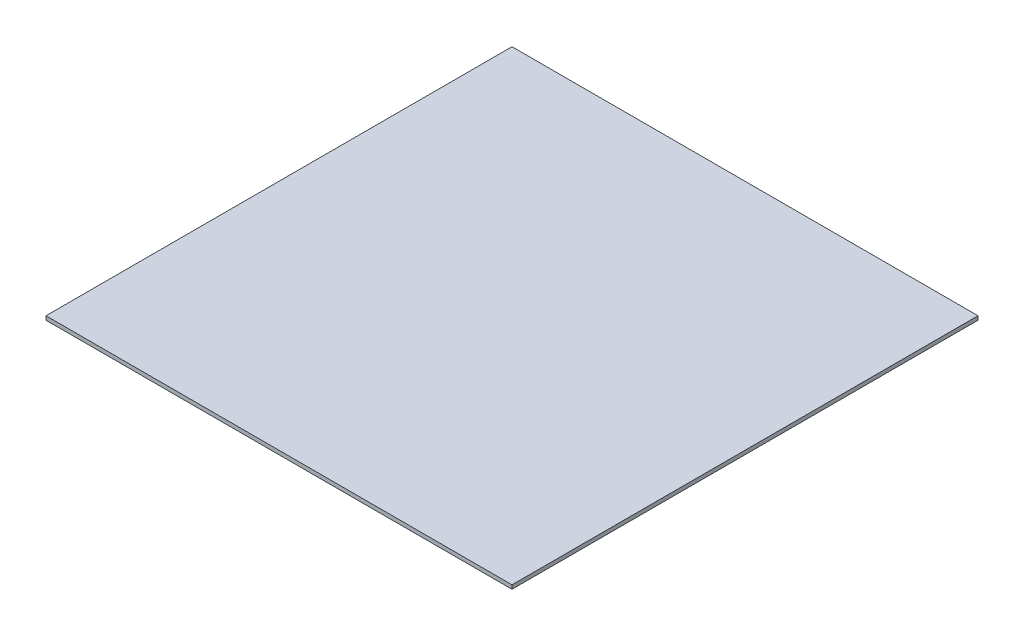
SolidWorks part; units mm, degrees
ref_plane "Front Plane" through (0, 0, 0) normal (0, 0, 1) x (1, 0, 0)
ref_plane "Top Plane" through (0, 0, 0) normal (0, 1, 0) x (1, 0, 0)
ref_plane "Right Plane" through (0, 0, 0) normal (1, 0, 0) x (0, 0, -1)
sketch "Sketch1" plane through (0, 0, 0) normal (0, 1, 0) x (1, 0, 0)
  line L1 (-32.2394, 74.2088) -> (348.7606, 74.2088)
  line L2 (-32.2394, 74.2088) -> (-32.2394, -306.7912)
  line L3 (-32.2394, -306.7912) -> (348.7606, -306.7912)
  line L4 (348.7606, 74.2088) -> (348.7606, -306.7912)
  dimension "D1" = 381
  dimension "D2" = 381
extrude "Boss-Extrude1" add sketch "Sketch1" along normal blind 3.175
